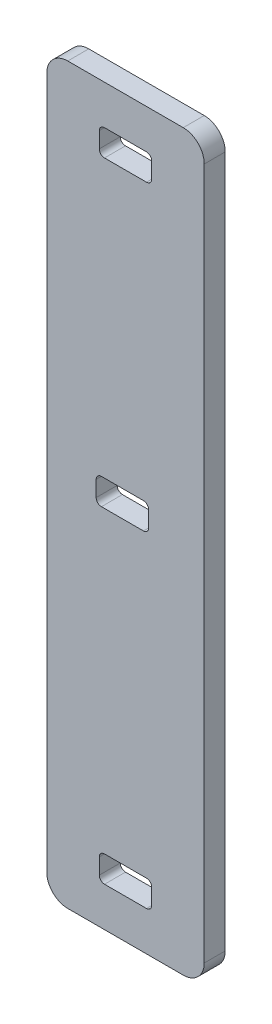
SolidWorks part; units mm, degrees
ref_plane "Plan de face" through (0, 0, 0) normal (0, 0, 1) x (1, 0, 0)
ref_plane "Plan de dessus" through (0, 0, 0) normal (0, 1, 0) x (1, 0, 0)
ref_plane "Plan de droite" through (0, 0, 0) normal (1, 0, 0) x (0, 0, -1)
sketch "Esquisse1" plane through (0, 0, 0) normal (0, 0, 1) x (1, 0, 0)
  line L1 (-11, -69.915) -> (11, -69.915)
  line L2 (-15, -65.915) -> (-15, 65.915)
  line L3 (-11, 69.915) -> (11, 69.915)
  line L4 (15, -65.915) -> (15, 65.915)
  line L5 (-15, -69.915) -> (15, 69.915) construction
  line L6 (-15, 69.915) -> (15, -69.915) construction
  arc A0 (-11, -69.915) -> (-15, -65.915) centre (-11, -65.915) cw
  arc A1 (11, -69.915) -> (15, -65.915) centre (11, -65.915) ccw
  arc A2 (-15, 65.915) -> (-11, 69.915) centre (-11, 65.915) cw
  arc A3 (11, 69.915) -> (15, 65.915) centre (11, 65.915) cw
  point P0 (0, 0)
  dimension "D3" = 4
  dimension "D1" = 139.83
  dimension "D2" = 30
extrude "Boss.-Extru.1" add sketch "Esquisse1" along normal blind 4
sketch "Esquisse2" plane through (0, 0, 4) normal (0, 0, 1) x (1, 0, 0)
  line L0 (11, 69.915) -> (-11, 69.915) construction
  line L1 (-4, -57.415) -> (4, -57.415)
  line L2 (-5, -58.415) -> (-5, -61.415)
  line L3 (-4, -62.415) -> (4, -62.415)
  line L4 (5, -58.415) -> (5, -61.415)
  line L5 (-5, -57.415) -> (5, -62.415) construction
  line L6 (-5, -62.415) -> (5, -57.415) construction
  line L7 (-4, 62.415) -> (4, 62.415)
  line L8 (-5, 61.415) -> (-5, 58.415)
  line L9 (-4, 57.415) -> (4, 57.415)
  line L10 (5, 61.415) -> (5, 58.415)
  line L11 (-5, 62.415) -> (5, 57.415) construction
  line L12 (-5, 57.415) -> (5, 62.415) construction
  line L13 (-11, -69.915) -> (11, -69.915) construction
  line L14 (-4.5876, 4.585) -> (3.4124, 4.585)
  line L15 (-15, 65.915) -> (-15, -65.915) construction
  line L16 (-5.5876, 3.585) -> (-5.5876, 0.585)
  line L17 (-4.5876, -0.415) -> (3.4124, -0.415)
  line L18 (4.4124, 3.585) -> (4.4124, 0.585)
  line L19 (-5.5876, 4.585) -> (4.4124, -0.415) construction
  line L20 (-5.5876, -0.415) -> (4.4124, 4.585) construction
  line L22 (-11, -69.915) -> (11, -69.915) construction
  arc A0 (-4, 62.415) -> (-5, 61.415) centre (-4, 61.415) ccw
  arc A1 (-5, 58.415) -> (-4, 57.415) centre (-4, 58.415) ccw
  arc A2 (4, 57.415) -> (5, 58.415) centre (4, 58.415) ccw
  arc A3 (4, 62.415) -> (5, 61.415) centre (4, 61.415) cw
  arc A4 (-4, -57.415) -> (-5, -58.415) centre (-4, -58.415) ccw
  arc A5 (-5, -61.415) -> (-4, -62.415) centre (-4, -61.415) ccw
  arc A6 (4, -62.415) -> (5, -61.415) centre (4, -61.415) ccw
  arc A7 (4, -57.415) -> (5, -58.415) centre (4, -58.415) cw
  arc A8 (-4.5876, 4.585) -> (-5.5876, 3.585) centre (-4.5876, 3.585) ccw
  arc A9 (-5.5876, 0.585) -> (-4.5876, -0.415) centre (-4.5876, 0.585) ccw
  arc A10 (3.4124, -0.415) -> (4.4124, 0.585) centre (3.4124, 0.585) ccw
  arc A11 (3.4124, 4.585) -> (4.4124, 3.585) centre (3.4124, 3.585) cw
  point P0 (0, -59.915)
  point P5 (0, 59.915)
  point P14 (0, 0)
  point P41 (-0.5876, 2.085)
  dimension "D9" = 1
  dimension "D10" = 1
  dimension "D11" = 1
  dimension "D1" = 7.5
  dimension "D2" = 7.5
  dimension "D3" = 5
  dimension "D4" = 5
  dimension "D5" = 10
  dimension "D6" = 15
  dimension "D7" = 10
  dimension "D8" = 15
  dimension "D12" = 69.5
extrude "Enlèv. mat.-Extru.1" cut sketch "Esquisse2" against normal through all
